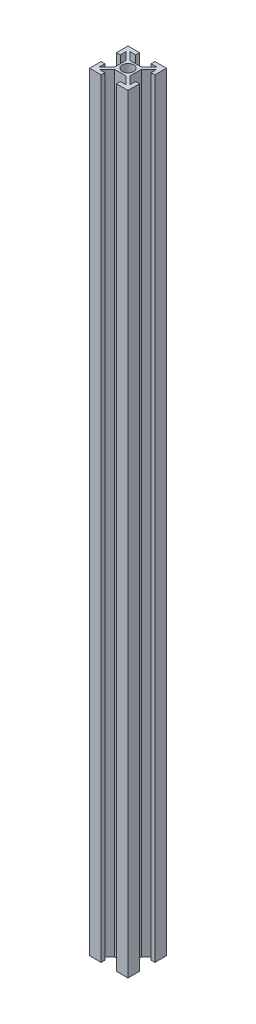
SolidWorks part; units mm, degrees
material "1060 Alloy"
ref_plane "Front Plane" through (0, 0, 0) normal (0, 0, 1) x (1, 0, 0)
ref_plane "Top Plane" through (0, 0, 0) normal (0, 1, 0) x (1, 0, 0)
ref_plane "Right Plane" through (0, 0, 0) normal (1, 0, 0) x (0, 0, -1)
sketch "2020 sketch" plane through (0, 0, 0) normal (0, 1, 0) x (1, 0, 0)
  line L0 (-4, 10) -> (-4, 8)
  line L1 (-10, 10) -> (-4, 10)
  line L2 (-10, 10) -> (-10, 4)
  line L3 (-10, -10) -> (-4, -10)
  line L4 (10, 10) -> (10, 4)
  line L5 (-10, 10) -> (10, -10) construction
  line L6 (-10, -10) -> (10, 10) construction
  line L7 (-4, 8) -> (-7, 8)
  line L8 (-7, 8) -> (-3, 4)
  line L9 (-3, 4) -> (3, 4)
  line L10 (3, 4) -> (7, 8)
  line L11 (7, 8) -> (4, 8)
  line L12 (4, 8) -> (4, 10)
  line L13 (4, 3) -> (4, -3)
  line L14 (8, 7) -> (4, 3)
  line L15 (8, 4) -> (8, 7)
  line L16 (10, 4) -> (8, 4)
  line L17 (8, -4) -> (10, -4)
  line L18 (8, -7) -> (8, -4)
  line L19 (4, -3) -> (8, -7)
  line L20 (3, -4) -> (-3, -4)
  line L21 (7, -8) -> (3, -4)
  line L22 (4, -8) -> (7, -8)
  line L23 (4, -10) -> (4, -8)
  line L24 (-4, -8) -> (-4, -10)
  line L25 (-7, -8) -> (-4, -8)
  line L26 (-3, -4) -> (-7, -8)
  line L27 (-4, -3) -> (-4, 3)
  line L28 (-8, -7) -> (-4, -3)
  line L29 (-8, -4) -> (-8, -7)
  line L30 (-10, -4) -> (-8, -4)
  line L31 (-8, 4) -> (-10, 4)
  line L32 (-8, 7) -> (-8, 4)
  line L33 (-4, 3) -> (-8, 7)
  line L34 (-10, -4) -> (-10, -10)
  line L35 (10, -4) -> (10, -10)
  line L36 (4, 10) -> (10, 10)
  line L37 (4, -10) -> (10, -10)
  circle A0 centre (0, 0) radius 3
  point P0 (0, 0)
  point P14 (4, 9)
  point P42 (0, 0)
  dimension "D9" = 6
  dimension "D1" = 20
  dimension "D2" = 20
  dimension "D3" = 8
  dimension "D4" = 6
  dimension "D5" = 6
  dimension "D6" = 2
  dimension "D7" = 4
  dimension "D8" = 4
extrude "Boss-Extrude1" add sketch "2020 sketch" along normal blind 400 contours A0 | L28 L27 L33 L32 L31 L2 L1 L0 L7 L8 L9 L10 L11 L12 L36 L4 L16 L15 L14 L13 L19 L18 L17 L35 L37 L23 L22 L21 L20 L26 L25 L24 L3 L34 L30 L29
